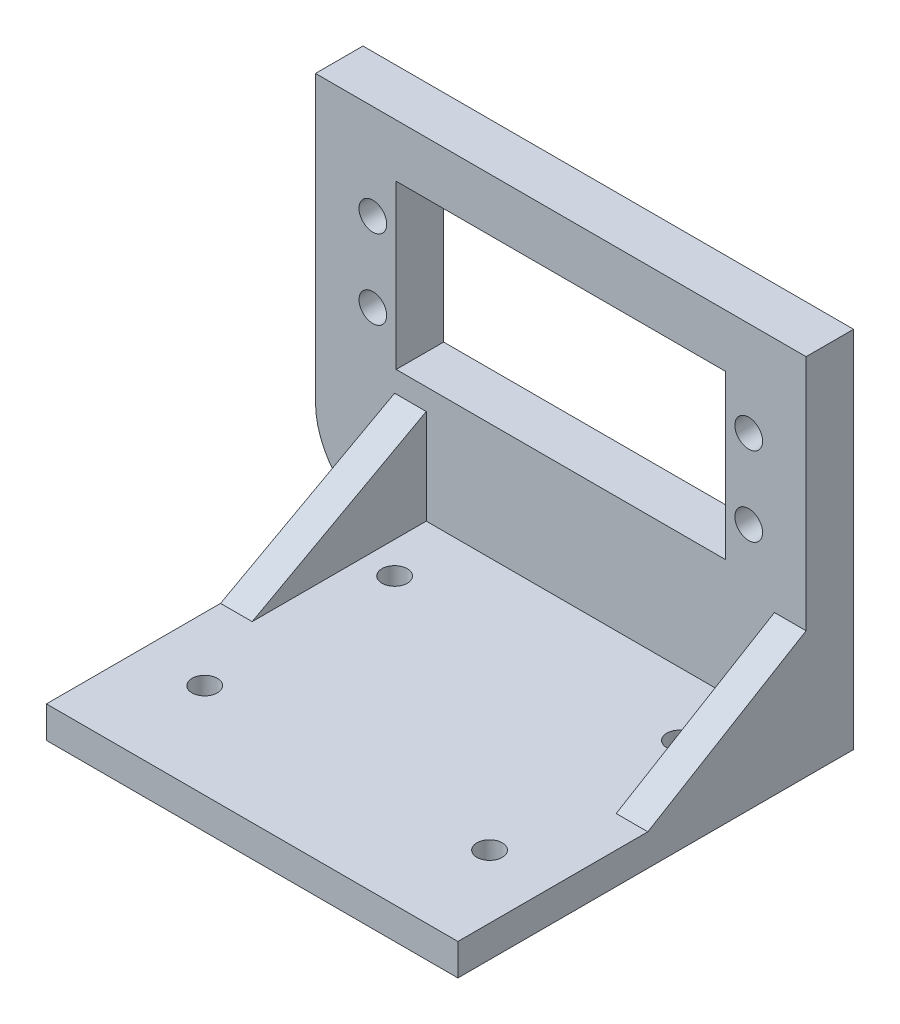
SolidWorks part; units mm, degrees
ref_plane "Piano frontale" through (0, 0, 0) normal (0, 0, 1) x (1, 0, 0)
ref_plane "Piano superiore" through (0, 0, 0) normal (0, 1, 0) x (1, 0, 0)
ref_plane "Piano destro" through (0, 0, 0) normal (1, 0, 0) x (0, 0, -1)
sketch "Schizzo1" plane through (0, 0, 0) normal (0, 1, 0) x (1, 0, 0)
  line L0 (0, -7.6596) -> (0, 9.4894) construction
  line L1 (-10.7234, 0) -> (11.5319, 0) construction
  line L3 (-31, 2.9362) -> (31, 2.9362)
  line L4 (-31, 2.9362) -> (-31, -3.0638)
  line L5 (-31, -3.0638) -> (31, -3.0638)
  line L6 (31, 2.9362) -> (31, -3.0638)
  dimension "D1" = 6
  dimension "D2" = 62
extrude "Estrusione-Estrusione1" add sketch "Schizzo1" along normal blind 46
sketch "Schizzo3" plane through (0, 0, 0) normal (0, 0, 1) x (1, 0, 0)
  line L0 (0, 0) -> (0, 44.017) construction
  line L2 (-20.8, 39.3) -> (20.8, 39.3)
  line L3 (-20.8, 39.3) -> (-20.8, 18.7)
  line L4 (-20.8, 18.7) -> (20.8, 18.7)
  line L5 (20.8, 39.3) -> (20.8, 18.7)
  line L6 (-20.8, 29) -> (34.4075, 29) construction
  line L7 (-31, 0) -> (31, 0) construction
  line L8 (-20.8, 29) -> (-30.2396, 29) construction
  dimension "D1" = 20.8
  dimension "D2" = 41.6
  dimension "D3" = 20.6
  dimension "D4" = 29
extrude "Taglio-Estrusione1" cut sketch "Schizzo3" against normal through all and the other way through all contours L3 L4 L5 L2
sketch "Schizzo6" plane through (0, 0, 3.0638) normal (0, 0, 1) x (1, 0, 0)
  line L0 (-20.8, 39.3) -> (-20.8, 18.7) construction
  line L1 (0, 0) -> (0, 44.0828) construction
  line L2 (-20.8, 29) -> (30.1753, 29) construction
  line L3 (-20.8, 29) -> (-28.6778, 29) construction
  line L4 (20.8, 39.3) -> (20.8, 18.7) construction
  line L5 (-20.8, 39.3) -> (20.8, 39.3) construction
  line L6 (-20.8, 18.7) -> (20.8, 18.7) construction
  circle A0 centre (-23.75, 34) radius 1.75
  circle A1 centre (-23.75, 24) radius 1.75
  circle A2 centre (23.75, 24) radius 1.75
  circle A3 centre (23.75, 34) radius 1.75
  dimension "D1" = 3.5
  dimension "D2" = 2.95
  dimension "D3" = 5
extrude "Taglio-Estrusione2" cut sketch "Schizzo6" against normal through all
sketch "Schizzo7" plane through (0, 0, 3.0638) normal (0, 0, 1) x (1, 0, 0)
  line L1 (31, 0) -> (-21, 0)
  line L2 (31, 0) -> (31, 4)
  line L3 (31, 4) -> (-21, 4)
  line L4 (-21, 0) -> (-21, 4)
  dimension "D1" = 52
  dimension "D2" = 4
extrude "Estrusione-Estrusione3" add sketch "Schizzo7" along normal blind 44
sketch "Schizzo10" plane through (0, 4, 0) normal (0, 1, 0) x (1, 0, 0)
  line L0 (5, -3.0638) -> (5, -47.0638) construction
  line L1 (31, -3.0638) -> (-21, -3.0638) construction
  line L2 (31, -47.0638) -> (-21, -47.0638) construction
  line L4 (-21, -47.0638) -> (-21, -3.0638) construction
  line L6 (31, 2.9362) -> (-31, 2.9362) construction
  line L7 (5, -25.0638) -> (-21, -25.0638) construction
  circle A0 centre (-13, -11.0638) radius 1.6
  circle A1 centre (-13, -35.0638) radius 1.6
  circle A2 centre (23, -35.0638) radius 1.6
  circle A3 centre (23, -11.0638) radius 1.6
  dimension "D1" = 3.2
  dimension "D6" = 3.2
  dimension "D2" = 8
  dimension "D3" = 14
  dimension "D4" = 24
  dimension "D5" = 36
extrude "Taglio-Estrusione4" cut sketch "Schizzo10" against normal through all contours A0 | A2 | A1 | A3
sketch "Schizzo13" plane through (31, 0, 0) normal (1, 0, 0) x (0, 0, -1)
  line L0 (-23.0638, 4) -> (-3.0638, 16)
  line L1 (-3.0638, 4) -> (-23.0638, 4)
  line L2 (-3.0638, 4) -> (-3.0638, 16)
  dimension "D1" = 12
  dimension "D2" = 20
extrude "Estrusione-Estrusione4" add sketch "Schizzo13" against normal blind 4
sketch "Schizzo15" plane through (-21, 0, 0) normal (-1, 0, 0) x (0, 0, 1)
  line L0 (47.0638, 4) -> (3.0638, 4) construction
  line L1 (25.0638, 4) -> (3.0638, 4)
  line L4 (3.0638, 4) -> (3.0638, 16)
  line L5 (3.0638, 16) -> (25.0638, 4)
extrude "Estrusione-Estrusione5" add sketch "Schizzo15" against normal blind 4
fillet "Raccordo3" radius 10 1 edges at (-31, 0, 0.0638)
